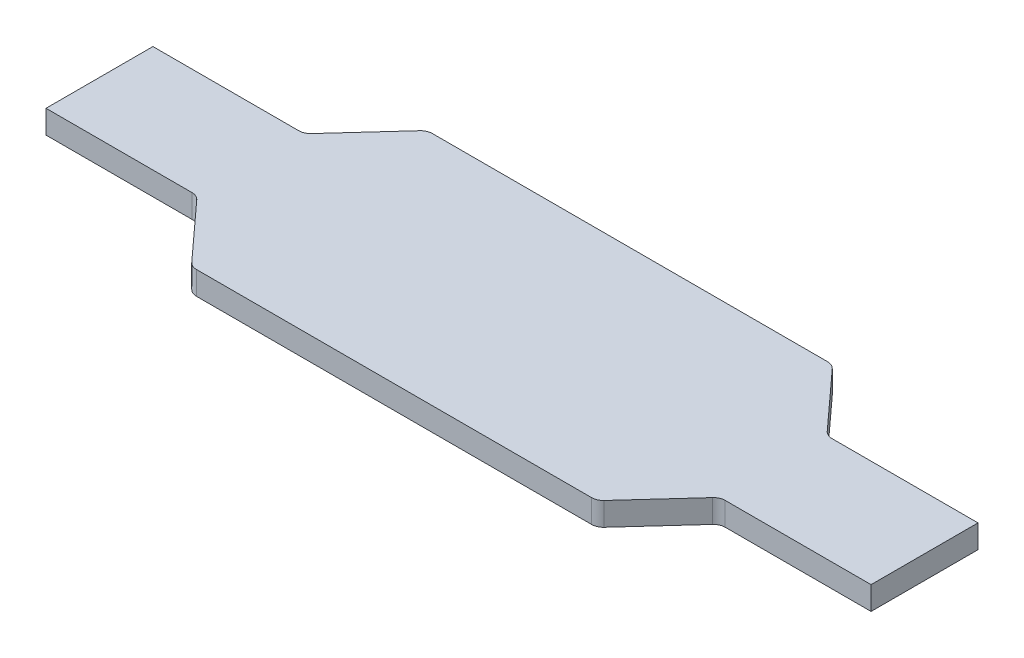
SolidWorks part; units mm, degrees
ref_plane "Front Plane" through (0, 0, 0) normal (0, 0, 1) x (1, 0, 0)
ref_plane "Top Plane" through (0, 0, 0) normal (0, 1, 0) x (1, 0, 0)
ref_plane "Right Plane" through (0, 0, 0) normal (1, 0, 0) x (0, 0, -1)
sketch "Sketch1" plane through (0, 0, 0) normal (0, 1, 0) x (1, 0, 0)
  line L0 (-130.3084, 61.4097) -> (39.6916, 61.4097)
  line L1 (43.3868, 59.7781) -> (65.6605, 35.3437)
  line L2 (69.3556, 33.7121) -> (132.1478, 33.7121)
  line L3 (132.1478, 33.7121) -> (132.1478, -12.2879)
  line L7 (69.3556, -12.2879) -> (132.1478, -12.2879)
  line L8 (43.3868, -38.3539) -> (65.6605, -13.9195)
  line L9 (-130.3084, -39.9855) -> (39.6916, -39.9855)
  line L10 (-134.0035, -38.3539) -> (-156.2772, -13.9195)
  line L11 (-159.9724, -12.2879) -> (-222.7646, -12.2879)
  line L13 (-222.7646, 33.7121) -> (-222.7646, -12.2879)
  line L14 (-159.9724, 33.7121) -> (-222.7646, 33.7121)
  line L15 (-134.0035, 59.7781) -> (-156.2772, 35.3437)
  arc A0 (39.6916, 61.4097) -> (43.3868, 59.7781) centre (39.6916, 56.4097) cw
  arc A1 (65.6605, -13.9195) -> (69.3556, -12.2879) centre (69.3556, -17.2879) cw
  arc A2 (65.6605, 35.3437) -> (69.3556, 33.7121) centre (69.3556, 38.7121) ccw
  arc A3 (39.6916, -39.9855) -> (43.3868, -38.3539) centre (39.6916, -34.9855) ccw
  arc A4 (-130.3084, -39.9855) -> (-134.0035, -38.3539) centre (-130.3084, -34.9855) cw
  arc A5 (-156.2772, 35.3437) -> (-159.9724, 33.7121) centre (-159.9724, 38.7121) cw
  arc A6 (-156.2772, -13.9195) -> (-159.9724, -12.2879) centre (-159.9724, -17.2879) ccw
  arc A7 (-130.3084, 61.4097) -> (-134.0035, 59.7781) centre (-130.3084, 56.4097) ccw
  point P14 (67.1478, 33.7121)
  point P23 (67.1478, -12.2879)
  point P38 (-157.7646, -12.2879)
  point P39 (-157.7646, 33.7121)
  dimension "D3" = 5
  dimension "D5" = 5
  dimension "D2" = 39
  dimension "D4" = 65
extrude "Boss-Extrude1" add sketch "Sketch1" along normal blind 10 contours L9 A3 L8 A1 L7 L3 L2 A2 L1 A0 L0 A7 L15 A5 L14 L13 L11 A6 L10 A4
